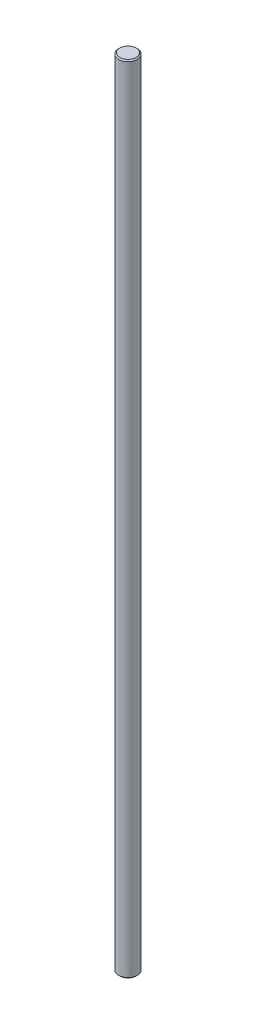
SolidWorks part; units mm, degrees
ref_plane "Front Plane" through (0, 0, 0) normal (0, 0, 1) x (1, 0, 0)
ref_plane "Top Plane" through (0, 0, 0) normal (0, 1, 0) x (1, 0, 0)
ref_plane "Right Plane" through (0, 0, 0) normal (1, 0, 0) x (0, 0, -1)
sketch "Sketch1" plane through (0, 0, 0) normal (0, 1, 0) x (1, 0, 0)
  circle A0 centre (0, 0) radius 4
  dimension "D1" = 8
extrude "Extrude1" add sketch "Sketch1" along normal blind 340
chamfer "Chamfer1" distance 0.5 angle 45 2 edges at (0, 340, 4) (0, 0, 4)
